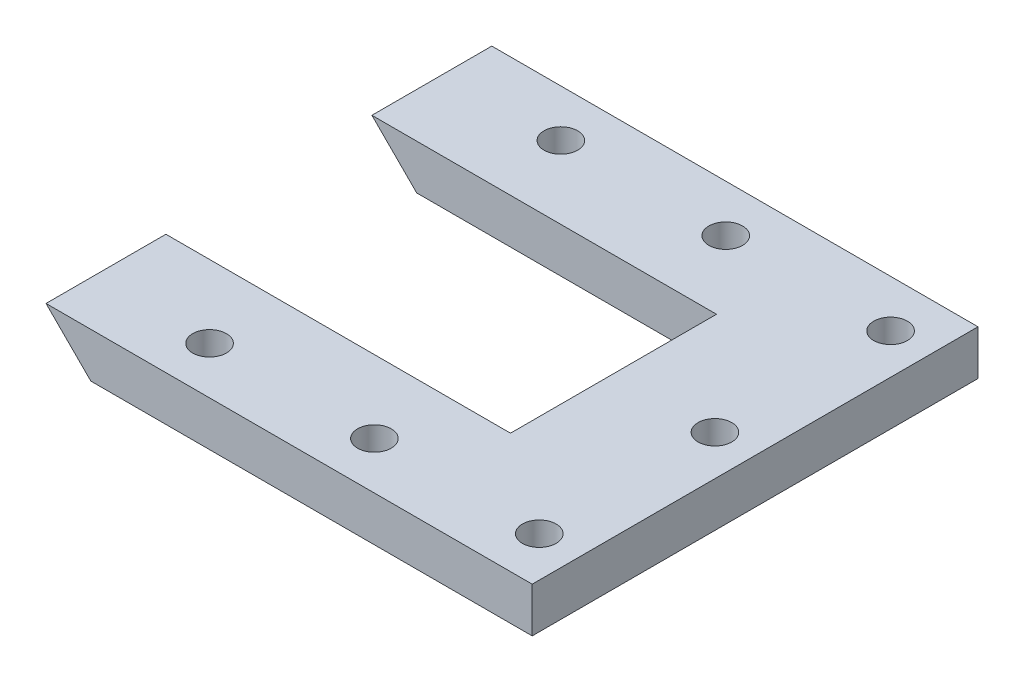
SolidWorks part; units mm, degrees
ref_plane "Front Plane" through (0, 0, 0) normal (0, 0, 1) x (1, 0, 0)
ref_plane "Top Plane" through (0, 0, 0) normal (0, 1, 0) x (1, 0, 0)
ref_plane "Right Plane" through (0, 0, 0) normal (1, 0, 0) x (0, 0, -1)
sketch "Sketch1" plane through (0, 0, 0) normal (0, 1, 0) x (1, 0, 0)
  line L1 (-51.4985, -47.2186) -> (51.4985, -47.2186)
  line L2 (-51.4985, -47.2186) -> (-51.4985, 47.2186)
  line L3 (-51.4985, 47.2186) -> (51.4985, 47.2186)
  line L4 (51.4985, -47.2186) -> (51.4985, 47.2186)
  line L5 (-51.4985, -47.2186) -> (51.4985, 47.2186) construction
  line L6 (-51.4985, 47.2186) -> (51.4985, -47.2186) construction
  point P0 (0, 0)
  dimension "D1" = 51.4985
  dimension "D2" = 47.2186
extrude "Boss-Extrude1" add sketch "Sketch1" along normal mid plane 9.4996
sketch "Sketch2" plane through (0, 0, 0) normal (0, 1, 0) x (1, 0, 0)
  line L1 (-154.4955, -21.8186) -> (21.5011, -21.8186)
  line L2 (-154.4955, -21.8186) -> (-154.4955, 21.8186)
  line L3 (-154.4955, 21.8186) -> (21.5011, 21.8186)
  line L4 (21.5011, -21.8186) -> (21.5011, 21.8186)
  point P8 (0, 0)
  dimension "D1" = 175.9966
  dimension "D2" = 43.6372
  dimension "D3" = 21.5011
  dimension "D4" = 21.8186
extrude "Cut-Extrude2" cut sketch "Sketch2" against normal through all from offset 4.7498
sketch "Sketch3" plane through (0, 0, 0) normal (0, 0, 1) x (1, 0, 0)
  line L0 (-154.4955, -14.2494) -> (-32.4993, -14.2494)
  line L1 (-32.4993, -14.2494) -> (-60.9981, 14.2494)
  line L2 (-60.9981, 14.2494) -> (-154.4955, 14.2494)
  line L3 (-154.4955, 14.2494) -> (-154.4955, -14.2494)
  point P4 (0, 0)
  dimension "D1" = 93.4974
  dimension "D2" = 121.9962
  dimension "D3" = 28.4988
  dimension "D4" = 154.4955
  dimension "D5" = 14.2494
extrude "Cut-Extrude6" cut sketch "Sketch3" against normal through all from offset 47.2186
sketch "Sketch4" plane through (0, 0, 0) normal (0, 1, 0) x (1, 0, 0)
  circle A0 centre (-26.8605, -37.211) radius 3.5687
  circle A1 centre (8.0645, -37.211) radius 3.5687
  circle A2 centre (42.9895, -37.211) radius 3.5687
  circle A3 centre (-26.8605, 37.211) radius 3.5687
  circle A4 centre (8.0645, 37.211) radius 3.5687
  circle A5 centre (42.9895, 37.211) radius 3.5687
  point P12 (0, 0)
  dimension "D1" = 7.1374
  dimension "D2" = 7.1374
  dimension "D3" = 7.1374
  dimension "D4" = 7.1374
  dimension "D5" = 7.1374
  dimension "D6" = 7.1374
  dimension "D7" = 34.925
  dimension "D8" = 69.85
  dimension "D9" = 74.422
  dimension "D10" = 42.9895
  dimension "D11" = 37.211
extrude "Cut-Extrude8" cut sketch "Sketch4" along normal through all from offset 4.7498
sketch "Sketch5" plane through (0, 0, 0) normal (0, 1, 0) x (1, 0, 0)
  circle A0 centre (42.9895, 0) radius 3.5687
  point P2 (0, 0)
  dimension "D1" = 7.1374
  dimension "D2" = 42.9895
extrude "Cut-Extrude10" cut sketch "Sketch5" along normal through all from offset 4.7498
